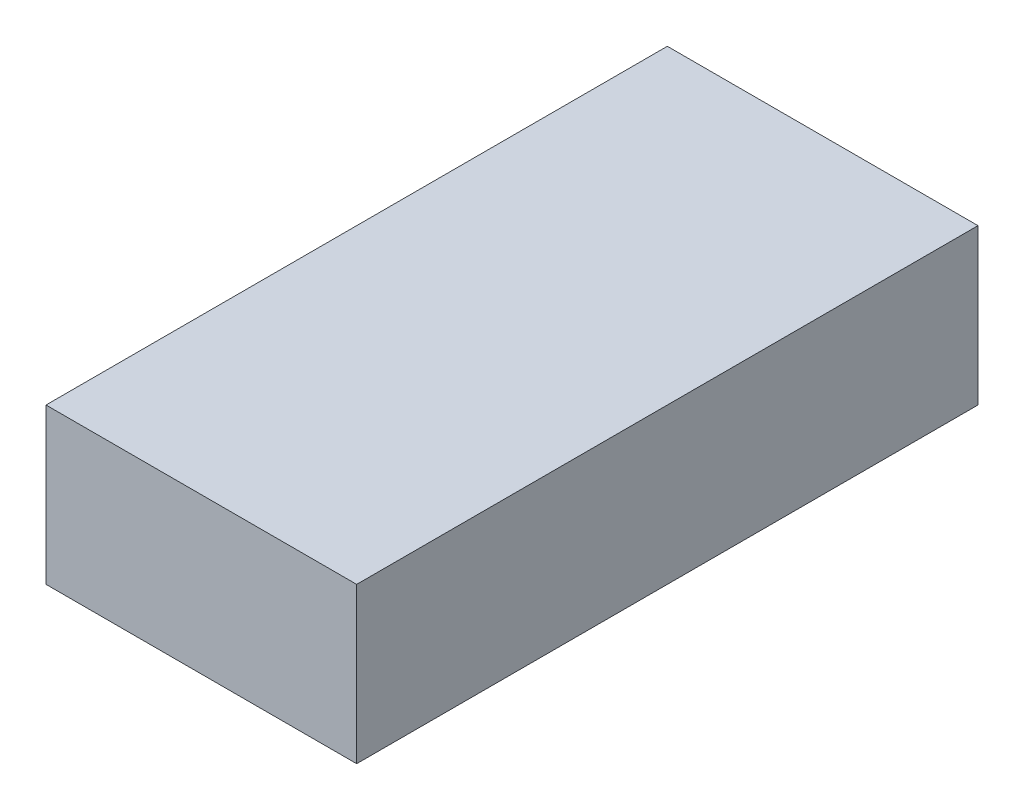
SolidWorks part; units mm, degrees
ref_plane "Alzado" through (0, 0, 0) normal (0, 0, 1) x (1, 0, 0)
ref_plane "Planta" through (0, 0, 0) normal (0, 1, 0) x (1, 0, 0)
ref_plane "Vista lateral" through (0, 0, 0) normal (1, 0, 0) x (0, 0, -1)
sketch "Croquis1" plane through (0, 0, 0) normal (0, 1, 0) x (1, 0, 0)
  line L1 (0, 0) -> (50, 0)
  line L2 (0, 0) -> (0, 100)
  line L3 (0, 100) -> (50, 100)
  line L4 (50, 0) -> (50, 100)
  dimension "D1" = 50
  dimension "D2" = 100
extrude "Saliente-Extruir1" add sketch "Croquis1" along normal blind 25
